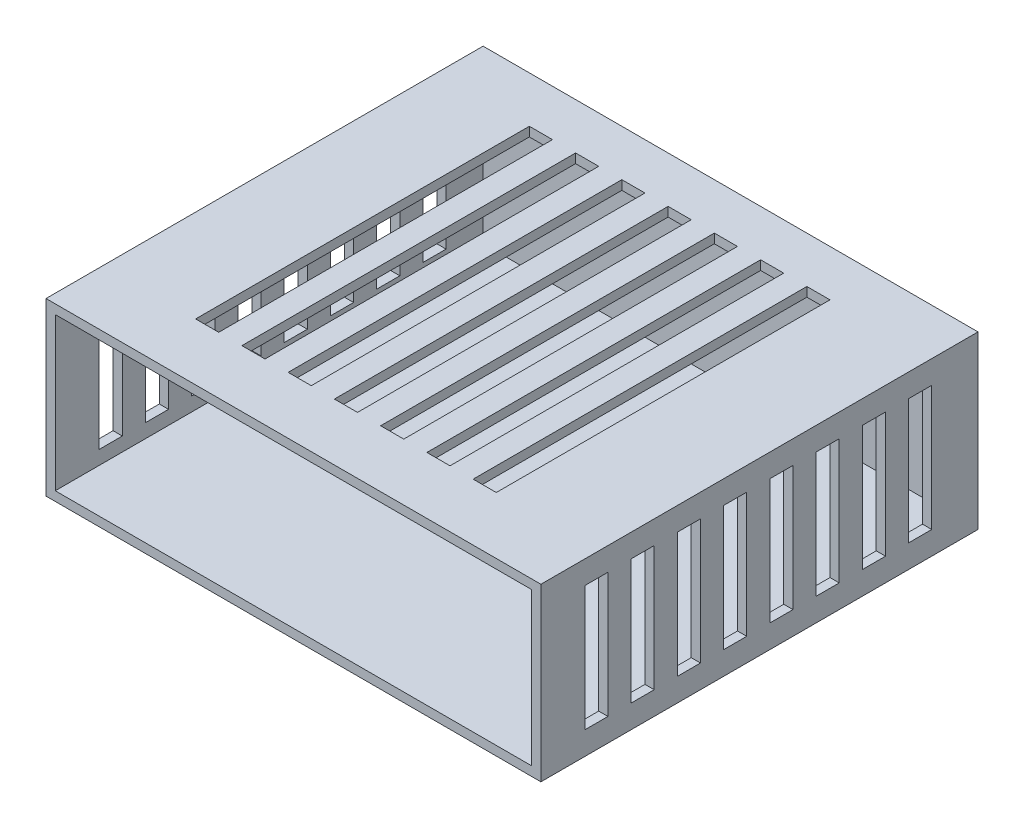
SolidWorks part; units mm, degrees
ref_plane "前视基准面" through (0, 0, 0) normal (0, 0, 1) x (1, 0, 0)
ref_plane "上视基准面" through (0, 0, 0) normal (0, 1, 0) x (1, 0, 0)
ref_plane "右视基准面" through (0, 0, 0) normal (1, 0, 0) x (0, 0, -1)
other "Configuration Table"
sketch "草图1" plane through (0, 0, 0) normal (0, 1, 0) x (1, 0, 0)
  line L1 (0, 0) -> (107, 0)
  line L2 (0, 0) -> (0, 94.5)
  line L3 (0, 94.5) -> (107, 94.5)
  line L4 (107, 0) -> (107, 94.5)
  dimension "D1" = 107
  dimension "D2" = 94.5
extrude "凸台-拉伸1" add sketch "草图1" along normal blind 37
shell "抽壳1" thickness 2
sketch "草图2" plane through (0, 37, 0) normal (0, 1, 0) x (1, 0, 0)
  line L0 (0, 94.5) -> (20, 94.5)
  line L1 (107, 94.5) -> (0, 94.5) construction
  line L2 (20, 94.5) -> (20, 84.5)
  line L3 (30, 84.5) -> (30, 12.3496)
  line L4 (30, 84.5) -> (35, 84.5)
  line L5 (35, 84.5) -> (35, 12.3496)
  line L6 (20, 84.5) -> (25, 84.5)
  line L7 (20, 84.5) -> (20, 12.3496)
  line L8 (20, 12.3496) -> (25, 12.3496)
  line L9 (25, 84.5) -> (25, 12.3496)
  line L10 (30, 12.3496) -> (35, 12.3496)
  line L11 (40, 84.5) -> (40, 12.3496)
  line L12 (40, 84.5) -> (45, 84.5)
  line L13 (45, 84.5) -> (45, 12.3496)
  line L14 (40, 12.3496) -> (45, 12.3496)
  line L15 (50, 84.5) -> (50, 12.3496)
  line L16 (50, 84.5) -> (55, 84.5)
  line L17 (55, 84.5) -> (55, 12.3496)
  line L18 (50, 12.3496) -> (55, 12.3496)
  line L19 (60, 84.5) -> (60, 12.3496)
  line L20 (60, 84.5) -> (65, 84.5)
  line L21 (65, 84.5) -> (65, 12.3496)
  line L22 (60, 12.3496) -> (65, 12.3496)
  line L23 (70, 84.5) -> (70, 12.3496)
  line L24 (70, 84.5) -> (75, 84.5)
  line L25 (75, 84.5) -> (75, 12.3496)
  line L26 (70, 12.3496) -> (75, 12.3496)
  line L27 (80, 84.5) -> (80, 12.3496)
  line L28 (80, 84.5) -> (85, 84.5)
  line L29 (85, 84.5) -> (85, 12.3496)
  line L30 (80, 12.3496) -> (85, 12.3496)
  line L31 (107, 0) -> (107, 94.5) construction
  point P35 (0, 0)
  point P36 (0, 0)
  dimension "D1" = 20
  dimension "D2" = 10
  dimension "D3" = 72.1504
  dimension "D4" = 5
  dimension "D6" = 22
  dimension "D5" = 7
extrude "切除-拉伸3" cut sketch "草图2" against normal blind 20 contours L9 L6 L7 L8 | L3 L10 L5 L4 | L11 L14 L13 L12 | L15 L18 L17 L16 | L19 L22 L21 L20 | L23 L26 L25 L24 | L27 L30 L29 L28
sketch "草图6" plane through (0, 0, 0) normal (-1, 0, 0) x (0, 0, 1)
  line L0 (-94.5, 37) -> (-84.5, 37)
  line L1 (-94.5, 37) -> (0, 37) construction
  line L3 (-84.5, 37) -> (-84.5, 32)
  line L5 (-74.5, 32) -> (-74.5, 5)
  line L6 (-84.5, 32) -> (-79.5, 32)
  line L7 (-84.5, 32) -> (-84.5, 5)
  line L8 (-84.5, 5) -> (-79.5, 5)
  line L9 (-79.5, 32) -> (-79.5, 5)
  line L10 (-74.5, 32) -> (-69.5, 32)
  line L11 (-69.5, 32) -> (-69.5, 5)
  line L12 (-74.5, 5) -> (-69.5, 5)
  line L13 (-64.5, 32) -> (-64.5, 5)
  line L14 (-64.5, 32) -> (-59.5, 32)
  line L15 (-59.5, 32) -> (-59.5, 5)
  line L16 (-64.5, 5) -> (-59.5, 5)
  line L17 (-54.5, 32) -> (-54.5, 5)
  line L18 (-54.5, 32) -> (-49.5, 32)
  line L19 (-49.5, 32) -> (-49.5, 5)
  line L20 (-54.5, 5) -> (-49.5, 5)
  line L21 (-44.5, 32) -> (-44.5, 5)
  line L22 (-44.5, 32) -> (-39.5, 32)
  line L23 (-39.5, 32) -> (-39.5, 5)
  line L24 (-44.5, 5) -> (-39.5, 5)
  line L25 (-34.5, 32) -> (-34.5, 5)
  line L26 (-34.5, 32) -> (-29.5, 32)
  line L27 (-29.5, 32) -> (-29.5, 5)
  line L28 (-34.5, 5) -> (-29.5, 5)
  line L29 (-24.5, 32) -> (-24.5, 5)
  line L30 (-24.5, 32) -> (-19.5, 32)
  line L31 (-19.5, 32) -> (-19.5, 5)
  line L32 (-24.5, 5) -> (-19.5, 5)
  line L33 (-14.5, 32) -> (-14.5, 5)
  line L34 (-14.5, 32) -> (-9.5, 32)
  line L35 (-9.5, 32) -> (-9.5, 5)
  line L36 (-14.5, 5) -> (-9.5, 5)
  dimension "D1" = 10
  dimension "D2" = 5
  dimension "D3" = 27
  dimension "D4" = 5
  dimension "D5" = 8
extrude "切除-拉伸4" cut sketch "草图6" against normal blind 1000 contours L9 L6 L7 L8 | L5 L12 L11 L10 | L13 L16 L15 L14 | L17 L20 L19 L18 | L21 L24 L23 L22 | L25 L28 L27 L26 | L29 L32 L31 L30 | L33 L36 L35 L34
